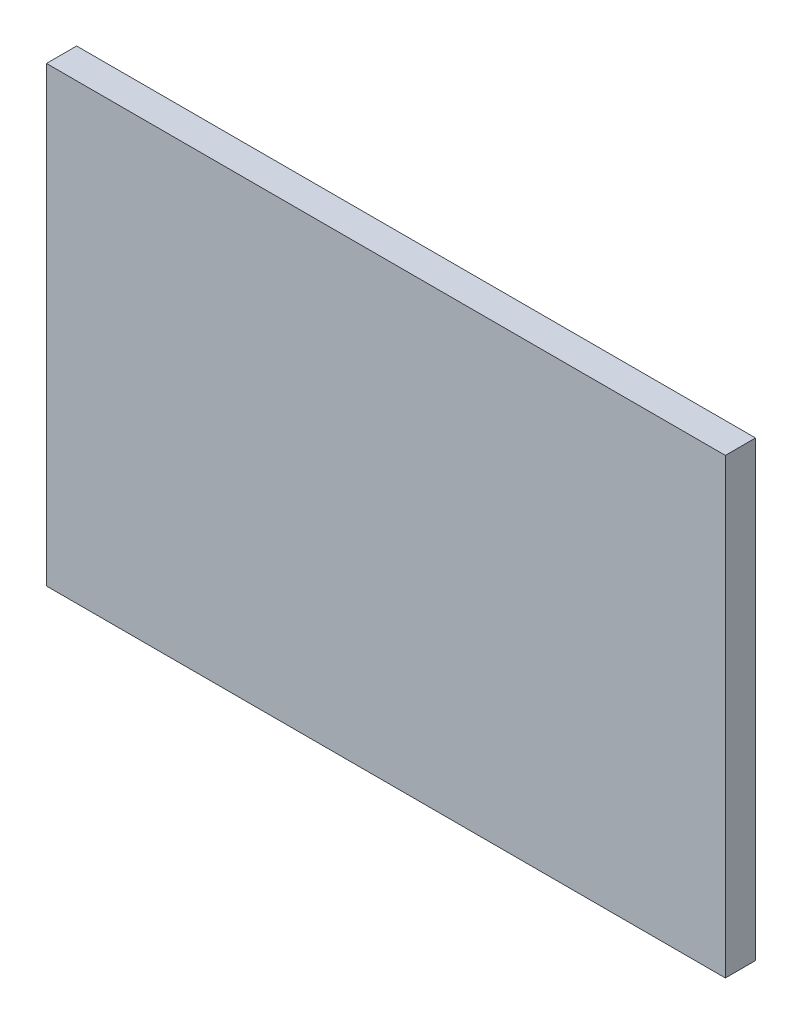
SolidWorks part; units mm, degrees
ref_plane "Front Plane" through (0, 0, 0) normal (0, 0, 1) x (1, 0, 0)
ref_plane "Top Plane" through (0, 0, 0) normal (0, 1, 0) x (1, 0, 0)
ref_plane "Right Plane" through (0, 0, 0) normal (1, 0, 0) x (0, 0, -1)
sketch "Sketch1" plane through (0, 0, 0) normal (0, 0, 1) x (1, 0, 0)
  line L1 (45, -30) -> (-45, -30)
  line L2 (45, -30) -> (45, 30)
  line L3 (45, 30) -> (-45, 30)
  line L4 (-45, -30) -> (-45, 30)
  line L5 (45, -30) -> (-45, 30) construction
  line L6 (45, 30) -> (-45, -30) construction
  point P0 (0, 0)
  dimension "D1" = 90
  dimension "D2" = 60
extrude "Boss-Extrude1" add sketch "Sketch1" along normal blind 4
